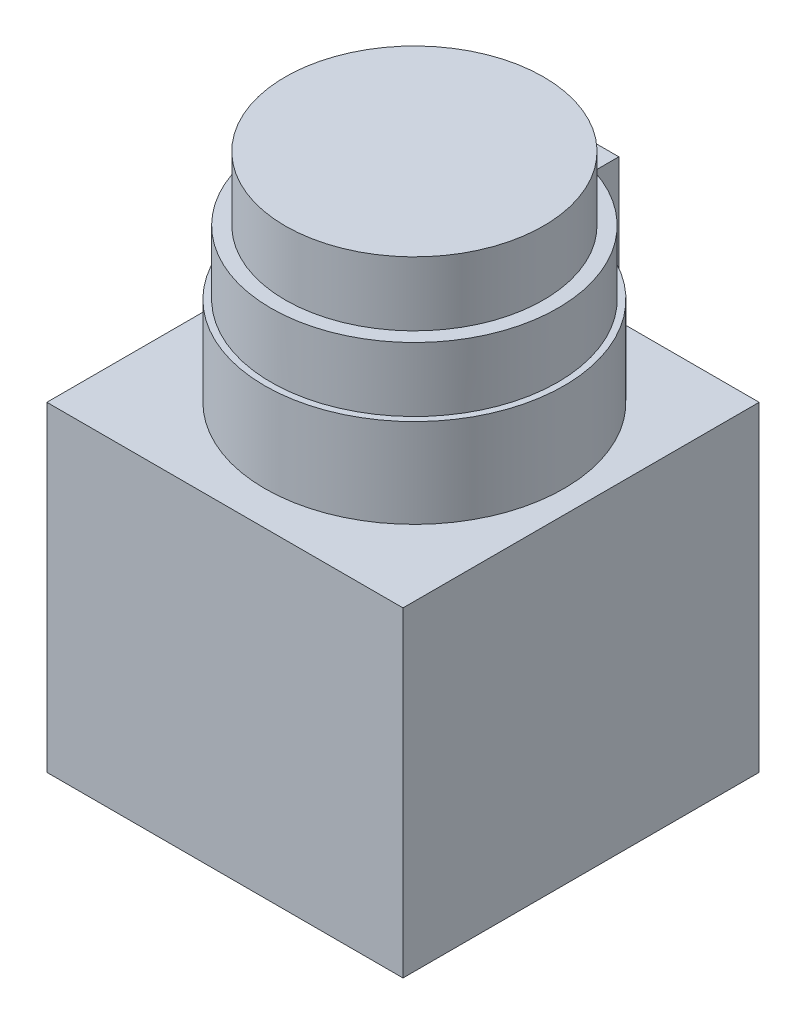
SolidWorks part; units mm, degrees
ref_plane "Front Plane" through (0, 0, 0) normal (0, 0, 1) x (1, 0, 0)
ref_plane "Top Plane" through (0, 0, 0) normal (0, 1, 0) x (1, 0, 0)
ref_plane "Right Plane" through (0, 0, 0) normal (1, 0, 0) x (0, 0, -1)
ref_plane "Plane1"
sketch "Sketch1" plane through (0, 0, 0) normal (0, 1, 0) x (-1, 0, 0)
  line L0 (-24.2, -24.2) -> (25.8, -24.2)
  line L1 (25.8, -24.2) -> (25.8, 25.8)
  line L2 (25.8, 25.8) -> (-24.2, 25.8)
  line L3 (-24.2, 25.8) -> (-24.2, -24.2)
  dimension "D1" = 50
  dimension "D2" = 50
extrude "Extrusion1" add sketch "Sketch1" along normal blind 45
sketch "Sketch2" plane through (0, 45, 0) normal (0, 1, 0) x (-1, 0, 0)
  circle A0 centre (0, 0) radius 21
  dimension "D1" = 42
extrude "Extrusion2" add sketch "Sketch2" along normal blind 12.5
sketch "Sketch3" plane through (0, 57.5, 0) normal (0, 1, 0) x (-1, 0, 0)
  circle A0 centre (0, 0) radius 20.1325
extrude "Extrusion3" add sketch "Sketch3" along normal blind 9
sketch "Sketch4" plane through (0, 66.5, 0) normal (0, 1, 0) x (-1, 0, 0)
  circle A0 centre (0, 0) radius 18.1325
extrude "Extrusion4" add sketch "Sketch4" along normal blind 9
ref_plane "Plane2"
sketch "Sketch5" plane through (0, 45, 0) normal (0, 1, 0) x (1, 0, 0)
  line L0 (-4.5, 24.2) -> (-4.5, 14)
  line L1 (-4.5, 14) -> (4.5, 14)
  line L2 (4.5, 14) -> (4.5, 24.2)
  line L3 (4.5, 24.2) -> (-4.5, 24.2)
  dimension "D1" = 9
extrude "Extrusion5" add sketch "Sketch5" along normal blind 20
hole_wizard "Hole1" positions "Sketch7" profile "Sketch6" legacy
sketch "Sketch7" plane through (0, 0, 0) normal (0, -1, 0) x (-1, 0, 0)
  line L0 (-24.2, 24.2) -> (25.8, 24.2) construction
  point P1 (-18.4201, -20.8)
  point P2 (21.5799, 19.2)
  dimension "D1" = 40
  dimension "D2" = 40
  dimension "D3" = 5
sketch "Sketch6" plane through (18.4201, 0, 20.8) normal (1, 0, 0) x (0, 0, -1)
  line L0 (0, 0) -> (0, 8.7511)
  line L1 (0, 8.7511) -> (1.25, 8)
  line L2 (1.25, 8) -> (1.25, 0)
  line L4 (1.25, 0) -> (0, 0)
  line L6 (0, 8.7511) -> (-1.25, 8) construction
  line L7 (0, -4.2442) -> (0, 117.3081) construction
  dimension "Diameter" = 2.5
  dimension "Depth" = 8
  dimension "Drill Angle" = 118
sketch "Sketch8" plane through (-25.8, 0, 0) normal (-1, 0, 0) x (0, 0, 1)
  line L0 (13.8, 6) -> (19.8, 6)
  line L1 (19.8, 6) -> (19.8, 3)
  line L2 (19.8, 3) -> (13.8, 3)
  line L3 (13.8, 3) -> (13.8, 6)
extrude "Extrusion6" cut sketch "Sketch8" against normal blind 5
fillet "Fillet1" radius 2 2 edges at (-23.3, 6, 19.8) (-23.3, 6, 13.8)
